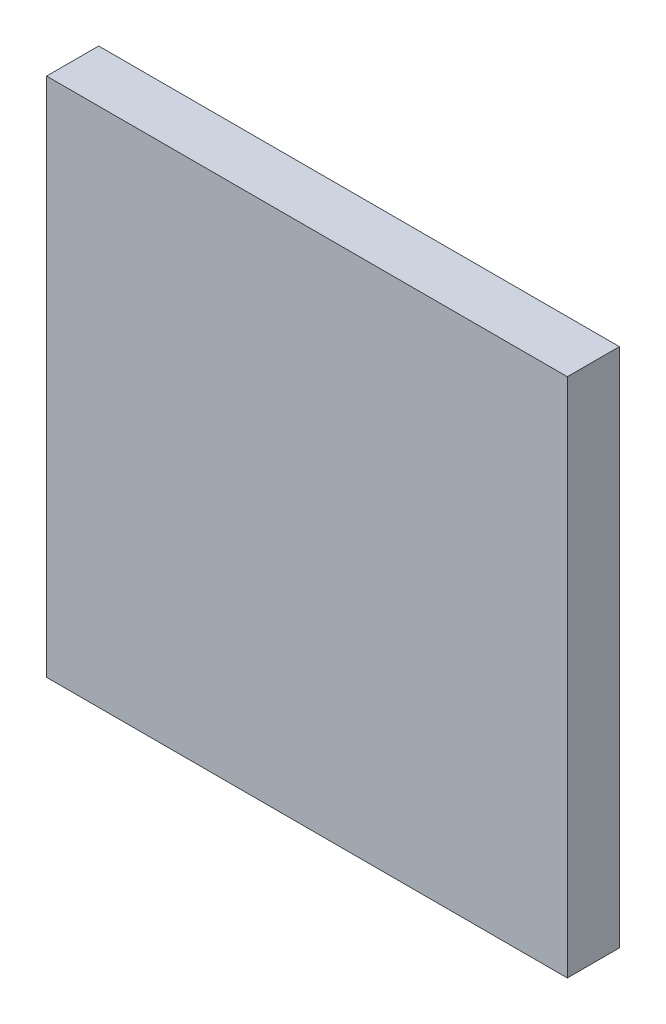
SolidWorks part; units mm, degrees
ref_plane "Front Plane" through (0, 0, 0) normal (0, 0, 1) x (1, 0, 0)
ref_plane "Top Plane" through (0, 0, 0) normal (0, 1, 0) x (1, 0, 0)
ref_plane "Right Plane" through (0, 0, 0) normal (1, 0, 0) x (0, 0, -1)
sketch "Sketch1" plane through (0, 0, 0) normal (0, 0, 1) x (1, 0, 0)
  line L1 (-50, 50) -> (50, 50)
  line L2 (-50, 50) -> (-50, -50)
  line L3 (-50, -50) -> (50, -50)
  line L4 (50, 50) -> (50, -50)
  line L5 (-50, 50) -> (50, -50) construction
  line L6 (-50, -50) -> (50, 50) construction
  point P0 (0, 0)
  dimension "D1" = 100
  dimension "D2" = 100
extrude "Boss-Extrude1" add sketch "Sketch1" along normal blind 10
